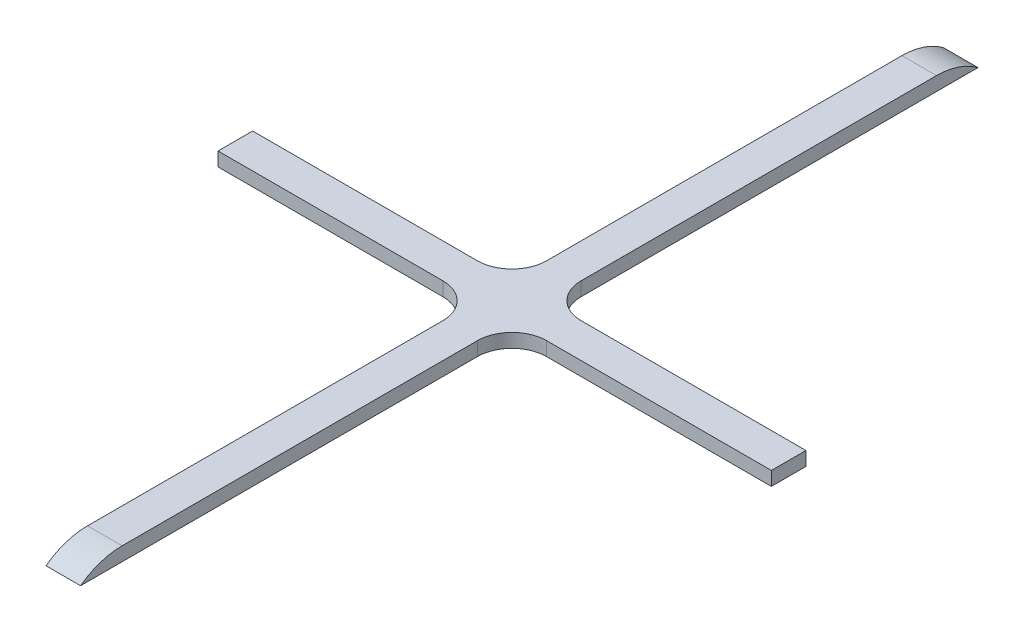
SolidWorks part; units mm, degrees
ref_plane "Front Plane" through (0, 0, 0) normal (0, 0, 1) x (1, 0, 0)
ref_plane "Top Plane" through (0, 0, 0) normal (0, 1, 0) x (1, 0, 0)
ref_plane "Right Plane" through (0, 0, 0) normal (1, 0, 0) x (0, 0, -1)
sketch "Sketch1" plane through (0, 0, 0) normal (1, 0, 0) x (0, 0, -1)
  line L0 (-75.25, 40) -> (160.25, 40) construction
  line L1 (-75.25, 40) -> (160.25, 40)
  line L2 (-87.25, 36) -> (172.25, 36)
  line L3 (-75.25, 36) -> (160.25, 36) construction
  arc A0 (170.7857, 3) -> (160.25, 40) centre (160.25, 20) ccw construction
  arc A1 (-75.25, 40) -> (-85.7857, 3) centre (-75.25, 20) ccw construction
  arc A2 (172.25, 36) -> (160.25, 40) centre (160.25, 20) ccw
  arc A3 (-75.25, 40) -> (-87.25, 36) centre (-75.25, 20) ccw
  arc A4 (-75.25, 40) -> (-85.7857, 3) centre (-75.25, 20) ccw construction
  arc A5 (170.7857, 3) -> (160.25, 40) centre (160.25, 20) ccw construction
  arc A6 (-75.25, 36) -> (-83.6785, 6.4) centre (-75.25, 20) ccw construction
  arc A7 (168.6785, 6.4) -> (160.25, 36) centre (160.25, 20) ccw construction
  dimension "D1" = 4
extrude "Boss-Extrude1" add sketch "Sketch1" along normal mid plane 10
sketch "Sketch2" plane through (0, 0, 0) normal (1, 0, 0) x (0, 0, -1)
  line L0 (42.5, 40) -> (42.5, 36) construction
  line L1 (160.25, 40) -> (-75.25, 40) construction
  line L2 (-87.25, 36) -> (172.25, 36) construction
  line L4 (37.5, 40) -> (47.5, 40)
  line L5 (37.5, 40) -> (37.5, 36)
  line L6 (37.5, 36) -> (47.5, 36)
  line L7 (47.5, 40) -> (47.5, 36)
  dimension "D1" = 10
  dimension "D2" = 5
extrude "Boss-Extrude2" add sketch "Sketch2" along normal mid plane 160
fillet "Fillet1" radius 10 4 edges at (5, 38, -37.5) (5, 38, -47.5) (-5, 38, -47.5) (-5, 38, -37.5)
